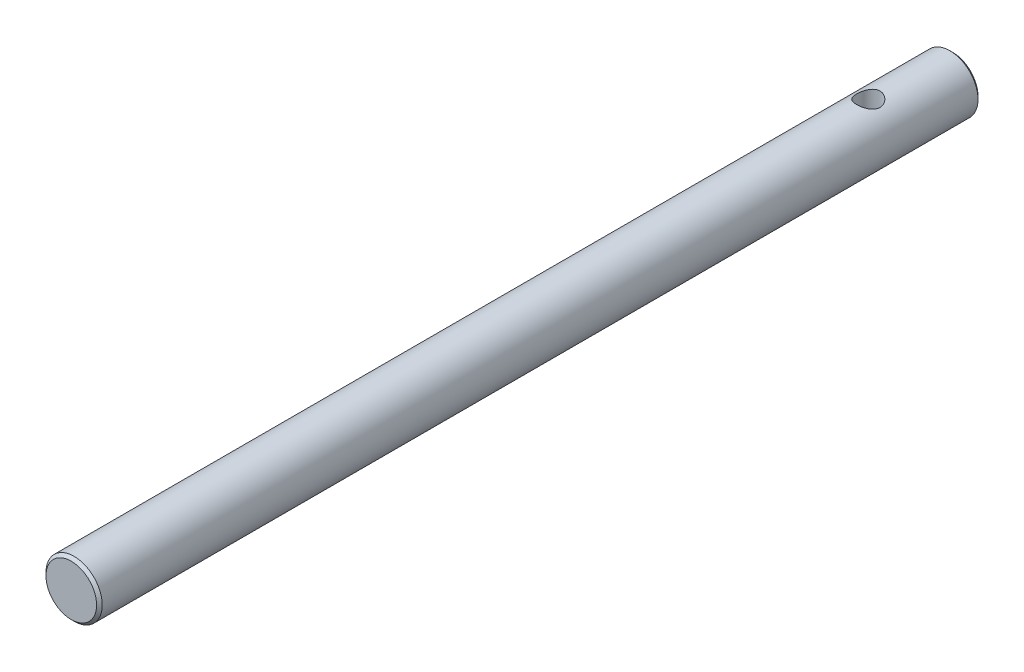
SolidWorks part; units mm, degrees
ref_plane "Front" through (0, 0, 0) normal (0, 0, 1) x (1, 0, 0)
ref_plane "Top" through (0, 0, 0) normal (0, 1, 0) x (1, 0, 0)
ref_plane "Right" through (0, 0, 0) normal (1, 0, 0) x (0, 0, -1)
sketch "Esquisse1" plane through (0, 0, 0) normal (0, 0, 1) x (1, 0, 0)
  circle A0 centre (0, 0) radius 2 construction
  circle A1 centre (0, 0) radius 3
  dimension "D1" = 6
  dimension "D2" = 4
extrude "Boss.-Extru.1" add sketch "Esquisse1" along normal blind 94
sketch "Esquisse2" plane through (0, 0, 0) normal (0, 1, 0) x (1, 0, 0)
  line L0 (-3, -94) -> (3, -94) construction
  line L1 (3, 0) -> (-3, 0) construction
  circle A0 centre (0, -9) radius 1.25
  dimension "D1" = 2.5
  dimension "D2" = 85
  dimension "D3" = 9
extrude "Enlèv. mat.-Extru.1" cut sketch "Esquisse2" against normal through all both and the other way through all
chamfer "Chanfrein1" distance 0.3 angle 45 2 edges at (3, 0, 94) (3, 0, 0)
